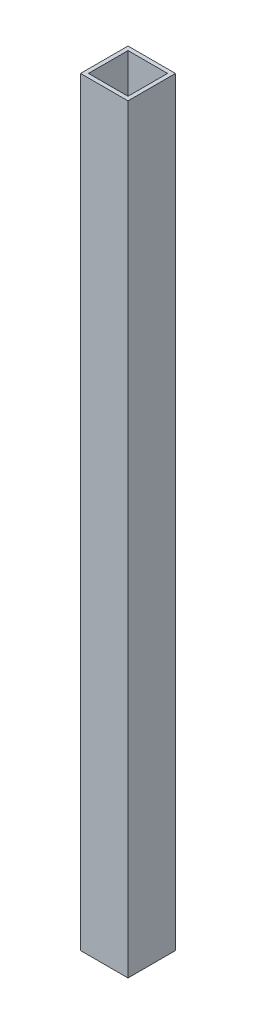
SolidWorks part; units mm, degrees
ref_plane "Front Plane" through (0, 0, 0) normal (0, 0, 1) x (1, 0, 0)
ref_plane "Top Plane" through (0, 0, 0) normal (0, 1, 0) x (1, 0, 0)
ref_plane "Right Plane" through (0, 0, 0) normal (1, 0, 0) x (0, 0, -1)
other "Configuration Table"
sketch "Sketch1" plane through (0, 0, 0) normal (0, 1, 0) x (1, 0, 0)
  line L1 (9.525, 9.525) -> (-9.525, 9.525)
  line L2 (9.525, 9.525) -> (9.525, -9.525)
  line L3 (9.525, -9.525) -> (-9.525, -9.525)
  line L4 (-9.525, 9.525) -> (-9.525, -9.525)
  line L5 (9.525, 9.525) -> (-9.525, -9.525) construction
  line L6 (9.525, -9.525) -> (-9.525, 9.525) construction
  line L7 (7.9375, -7.9375) -> (-7.9375, -7.9375)
  line L8 (7.9375, -7.9375) -> (7.9375, 7.9375)
  line L9 (7.9375, 7.9375) -> (-7.9375, 7.9375)
  line L10 (-7.9375, -7.9375) -> (-7.9375, 7.9375)
  line L11 (7.9375, -7.9375) -> (-7.9375, 7.9375) construction
  line L12 (7.9375, 7.9375) -> (-7.9375, -7.9375) construction
  point P0 (0, 0)
  point P6 (0, 0)
  dimension "D1" = 19.05
  dimension "D2" = 1.5875
extrude "Boss-Extrude1" add sketch "Sketch1" along normal blind 304.8
